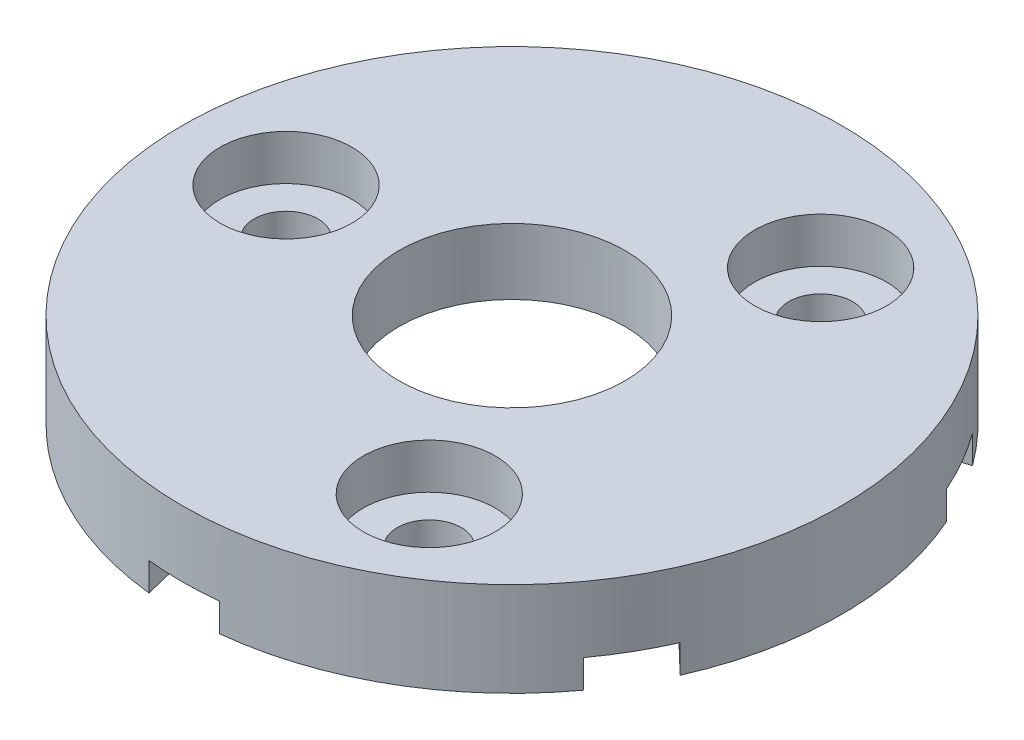
SolidWorks part; units mm, degrees
ref_plane "Front Plane" through (0, 0, 0) normal (0, 0, 1) x (1, 0, 0)
ref_plane "Top Plane" through (0, 0, 0) normal (0, 1, 0) x (1, 0, 0)
ref_plane "Right Plane" through (0, 0, 0) normal (1, 0, 0) x (0, 0, -1)
sketch "Sketch1" plane through (0, 0, 0) normal (0, 1, 0) x (1, 0, 0)
  circle A0 centre (0, 0) radius 17.5
  dimension "D1" = 35
extrude "Boss-Extrude1" add sketch "Sketch1" along normal blind 5
hole_wizard "CBORE for M3 Pan Head Screw1" positions "Sketch3" profile "Sketch2" counterbore size "M3" standard "ISO" end condition through all
sketch "Sketch3" plane through (0, 5, 0) normal (0, 1, 0) x (1, 0, 0)
  point P0 (-12, 0)
  dimension "D1" = 12
sketch "Sketch2" plane through (-12, 5, 0) normal (1, 0, 0) x (0, 0, 1)
  line L0 (0, 0) -> (0, 5)
  line L1 (0, 5) -> (1.7, 5)
  line L3 (1.7, 5) -> (1.7, 2.4)
  line L4 (1.7, 2.4) -> (3.5, 2.4)
  line L5 (3.5, 2.4) -> (3.5, 0)
  line L7 (3.5, 0) -> (0, 0)
  line L11 (0, -6.35) -> (0, 107.95) construction
  dimension "Thru Hole Dia." = 3.4
  dimension "Thru Hole Depth" = 5
  dimension "C'Bore Dia." = 7
  dimension "C'Bore Depth" = 2.4
pattern_circular "CirPattern1" count 3 over 360 about axis through (0, 0, 0) along (0, 1, 0) of "CBORE for M3 Pan Head Screw1"
hole_wizard "Ø12.0 (12) Diameter Hole1" positions "Sketch5" profile "Sketch6" hole size "Ø12.0" standard "ISO" end condition through all
sketch "Sketch5" plane through (0, 0, 0) normal (0, -1, 0) x (-1, 0, 0)
  point P0 (0, 0)
sketch "Sketch6" plane through (0, 0, 0) normal (1, 0, 0) x (0, 0, -1)
  line L0 (0, 0) -> (0, 5)
  line L1 (0, 5) -> (6, 5)
  line L2 (6, 5) -> (6, 0)
  line L5 (6, 0) -> (0, 0)
  line L11 (0, -6.35) -> (0, 107.95) construction
  dimension "Thru Hole Dia." = 12
  dimension "Thru Hole Depth" = 5
sketch "Sketch7" plane through (0, 0, 0) normal (0, -1, 0) x (1, 0, 0)
  line L0 (0, 0) -> (0, 25) construction
  line L1 (0, 25) -> (-5.7236, 1.8)
  line L2 (-5.7236, 1.8) -> (5.7236, 1.8)
  line L3 (5.7236, 1.8) -> (0, 25)
  circle A0 centre (0, 0) radius 6 construction
  dimension "D1" = 25
extrude "Cut-Extrude1" cut sketch "Sketch7" against normal blind 1.5
pattern_circular "CirPattern2" count 6 over 360 about axis through (0, 0, 0) along (0, 1, 0) of "Cut-Extrude1"
